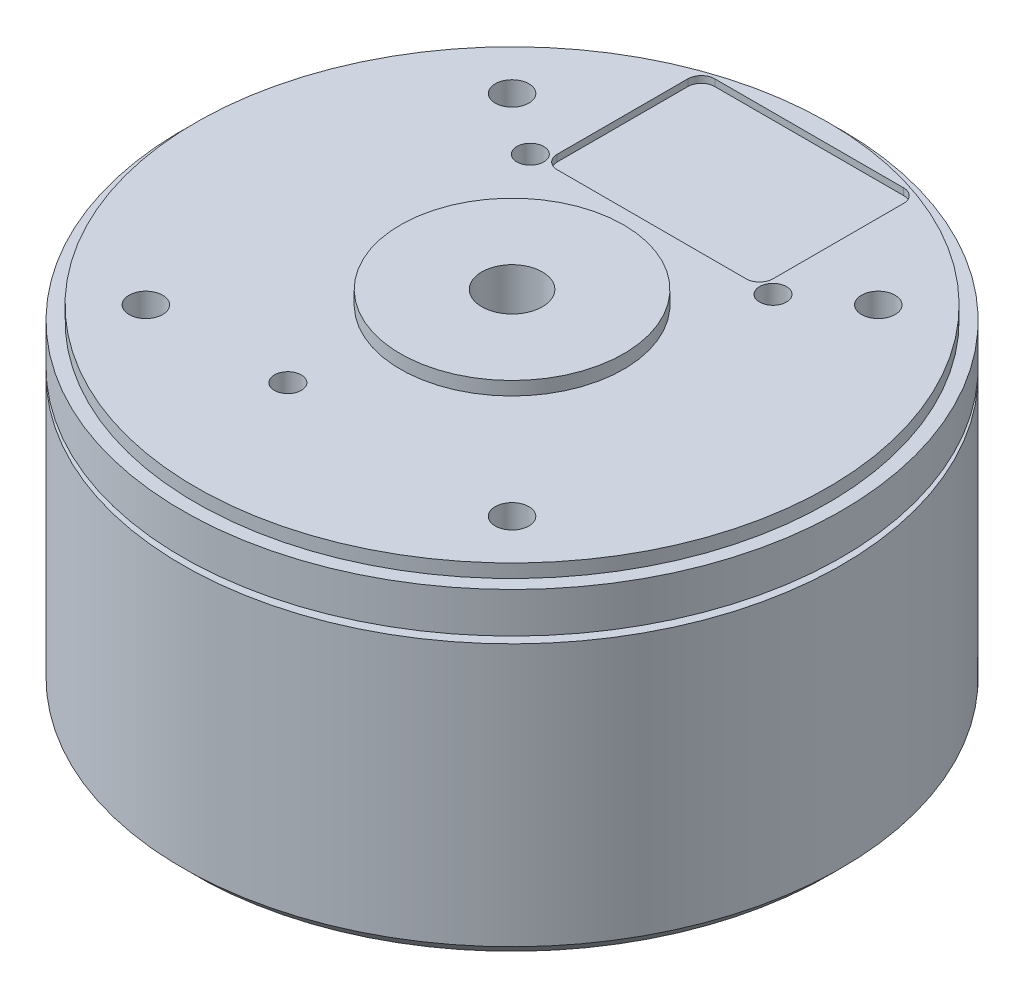
SolidWorks part; units mm, degrees
material "6061 合金"
ref_plane "前视基准面" through (0, 0, 0) normal (0, 0, 1) x (1, 0, 0)
ref_plane "上视基准面" through (0, 0, 0) normal (0, 1, 0) x (1, 0, 0)
ref_plane "右视基准面" through (0, 0, 0) normal (1, 0, 0) x (0, 0, -1)
sketch "草图1" plane through (0, 0, 0) normal (0, 0, 1) x (1, 0, 0)
  line L0 (0, 0) -> (0, 8.625) construction
  line L1 (2.25, 0) -> (2.25, 26)
  line L4 (2.25, 26) -> (8.3, 26)
  line L5 (8.3, 26) -> (8.3, 25)
  line L6 (8.3, 25) -> (23.5, 25)
  line L7 (23.5, 25) -> (23.5, 24)
  line L8 (23.5, 24) -> (24.5, 24)
  line L9 (24.5, 24) -> (24.5, 21)
  line L10 (24.5, 21) -> (23.5, 21)
  line L11 (23.5, 21) -> (23.5, 20.5)
  line L12 (23.5, 20.5) -> (24.5, 20.5)
  line L13 (24.5, 20.5) -> (24.5, 0)
  line L14 (24.5, 0) -> (2.25, 0)
  dimension "D1" = 4.5
  dimension "D2" = 49
  dimension "D3" = 47
  dimension "D4" = 25
  dimension "D5" = 1
  dimension "D6" = 16.6
  dimension "D7" = 1
  dimension "D8" = 0.5
  dimension "D11" = 3
revolve "旋转1" add sketch "草图1" angle 360 about L0
chamfer "倒角1" distance 1 angle 45 1 edges at (0, 0, -24.5)
sketch "草图2" plane through (0, 25, 0) normal (0, 1, 0) x (1, 0, 0)
  line L0 (0, -14.3) -> (0, 14.3) construction
  line L6 (0, 0) -> (0, -17.4509) construction
  circle A4 centre (13.6118, 13.6118) radius 1.25
  circle A6 centre (13.6118, -13.6118) radius 1.25
  circle A7 centre (-13.6118, -13.6118) radius 1.25
  circle A8 centre (-13.6118, 13.6118) radius 1.25
  circle A9 centre (-9.0208, 10.3773) radius 1
  circle A10 centre (0, 0) radius 13.75 construction
  circle A11 centre (-3.3264, -13.3416) radius 1
  circle A12 centre (9.0208, 10.3773) radius 1
  point P0 (0, 0)
  point P21 (0, 0)
  dimension "D3" = 82
  dimension "D4" = 2.5
  dimension "D5" = 4
  dimension "D6" = 38.5
  dimension "D1" = 27.5
  dimension "D2" = 2
  dimension "D7" = 14
extrude "切除-拉伸1" cut sketch "草图2" against normal blind 4
sketch "草图3" plane through (0, 0, 0) normal (0, -1, 0) x (1, 0, 0)
  circle A1 centre (0, 9.5) radius 1.5
  circle A2 centre (8.8388, 8.8388) radius 1.5
  circle A3 centre (9.5, 0) radius 1.5
  circle A4 centre (8.8388, -8.8388) radius 1.5
  circle A5 centre (0, -9.5) radius 1.5
  circle A6 centre (-8.8388, -8.8388) radius 1.5
  circle A7 centre (-9.5, 0) radius 1.5
  circle A8 centre (-8.8388, 8.8388) radius 1.5
  point P20 (0, 0)
  dimension "D1" = 3
  dimension "D2" = 3
  dimension "D4" = 25
  dimension "D5" = 19
  dimension "D3" = 4
extrude "切除-拉伸2" cut sketch "草图3" against normal blind 4
sketch "草图4" plane through (0, 0, 0) normal (0, -1, 0) x (1, 0, 0)
  circle A0 centre (0, 0) radius 6.3
  dimension "D1" = 12.6
extrude "切除-拉伸3" cut sketch "草图4" against normal blind 1
sketch "草图5" plane through (0, 25, 0) normal (0, 1, 0) x (1, 0, 0)
  line L1 (-7.0208, 10.3773) -> (7.0208, 10.3773)
  line L2 (-8.0208, 11.3773) -> (-8.0208, 21.0888)
  line L3 (-7.0208, 22.0888) -> (7.0208, 22.0888)
  line L4 (8.0208, 11.3773) -> (8.0208, 21.0888)
  line L5 (-8.0208, 10.3773) -> (8.0208, 22.0888) construction
  line L6 (-8.0208, 22.0888) -> (8.0208, 10.3773) construction
  arc A0 (7.0208, 22.0888) -> (8.0208, 21.0888) centre (7.0208, 21.0888) cw
  arc A1 (7.0208, 10.3773) -> (8.0208, 11.3773) centre (7.0208, 11.3773) ccw
  arc A2 (-7.0208, 10.3773) -> (-8.0208, 11.3773) centre (-7.0208, 11.3773) cw
  arc A3 (-8.0208, 21.0888) -> (-7.0208, 22.0888) centre (-7.0208, 21.0888) cw
  circle A4 centre (0, 0) radius 23.5 construction
  circle A5 centre (9.0208, 10.3773) radius 1 construction
  circle A6 centre (9.0208, 10.3773) radius 1 construction
  point P0 (0, 16.233)
  dimension "D1" = 1
extrude "切除-拉伸4" cut sketch "草图5" against normal blind 0.5
